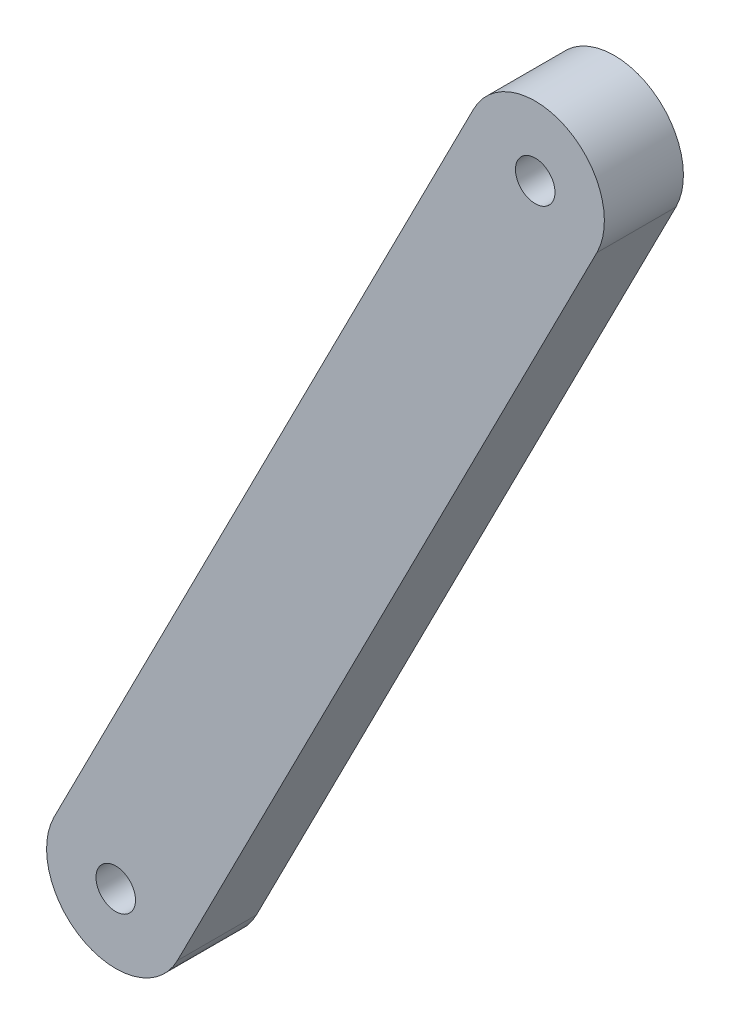
SolidWorks part; units mm, degrees
ref_plane "Спереди" through (0, 0, 0) normal (0, 0, 1) x (1, 0, 0)
ref_plane "Сверху" through (0, 0, 0) normal (0, 1, 0) x (1, 0, 0)
ref_plane "Справа" through (0, 0, 0) normal (1, 0, 0) x (0, 0, -1)
sketch "Sketch1" plane through (0, 0, 0) normal (0, 0, 1) x (1, 0, 0)
  line L0 (0, 0) -> (21.2293, 41.6403) construction
  line L1 (-3.1181, 1.5897) -> (18.1112, 43.23)
  line L2 (3.1181, -1.5897) -> (24.3475, 40.0506)
  arc A0 (-3.1181, 1.5897) -> (3.1181, -1.5897) centre (0, 0) ccw
  arc A1 (24.3475, 40.0506) -> (18.1112, 43.23) centre (21.2293, 41.6403) ccw
  circle A2 centre (21.2293, 41.6403) radius 1
  circle A3 centre (0, 0) radius 1
  point P3 (10.6147, 20.8202)
  dimension "D1" = 2
  dimension "D2" = 3.5
extrude "Boss-Extrude1" add sketch "Sketch1" along normal blind 4
